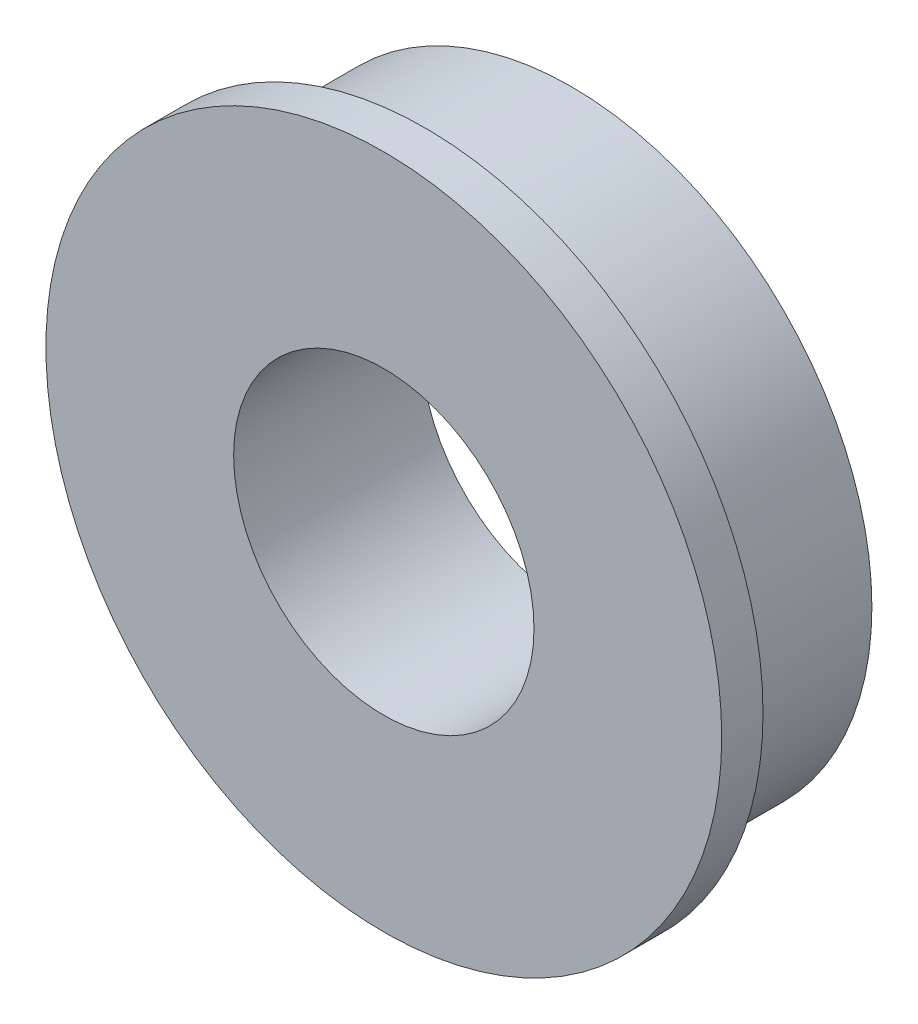
SolidWorks part; units mm, degrees
ref_plane "Alzado" through (0, 0, 0) normal (0, 0, 1) x (1, 0, 0)
ref_plane "Planta" through (0, 0, 0) normal (0, 1, 0) x (1, 0, 0)
ref_plane "Vista lateral" through (0, 0, 0) normal (1, 0, 0) x (0, 0, -1)
sketch "Croquis1" plane through (0, 0, 0) normal (0, 0, 1) x (1, 0, 0)
  circle A0 centre (0, 0) radius 9
extrude "Saliente-Extruir1" add sketch "Croquis1" along normal blind 1.1
sketch "Croquis2" plane through (0, 0, 0) normal (0, 0, -1) x (-1, 0, 0)
  circle A2 centre (0, 0) radius 8
  dimension "D1" = 16
extrude "Saliente-Extruir2" add sketch "Croquis2" along normal blind 3.9
sketch "Croquis3" plane through (0, 0, -3.9) normal (0, 0, -1) x (-1, 0, 0)
  circle A0 centre (0, 0) radius 4
extrude "Cortar-Extruir1" cut sketch "Croquis3" against normal blind 5
